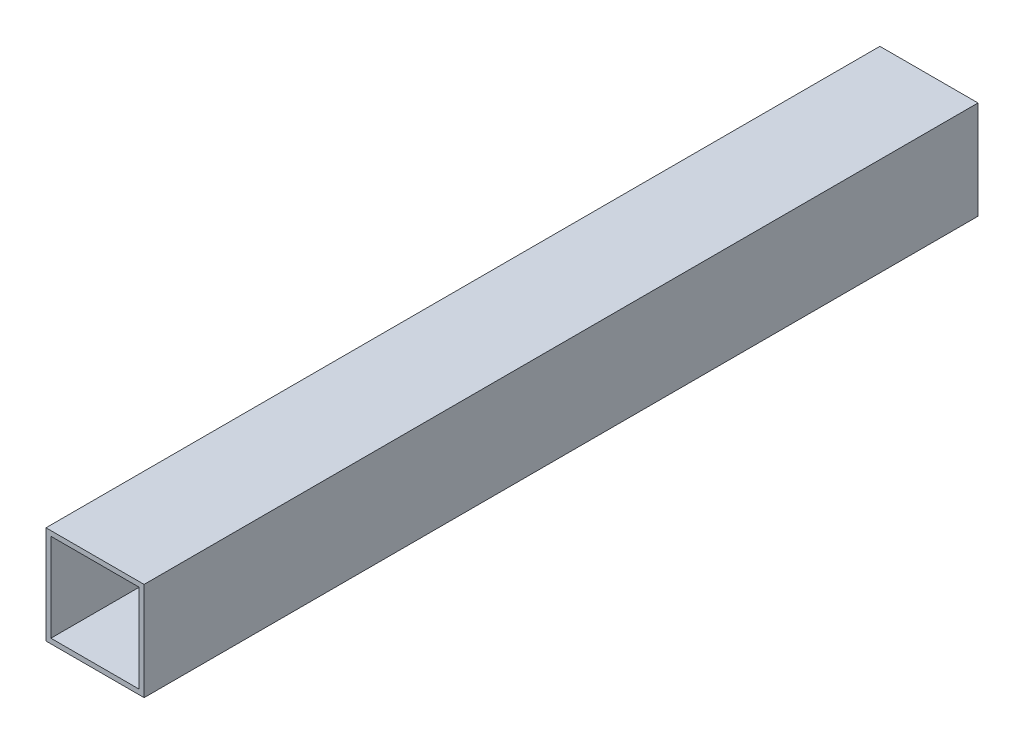
SolidWorks part; units mm, degrees
ref_plane "Alzado" through (0, 0, 0) normal (0, 0, 1) x (1, 0, 0)
ref_plane "Planta" through (0, 0, 0) normal (0, 1, 0) x (1, 0, 0)
ref_plane "Vista lateral" through (0, 0, 0) normal (1, 0, 0) x (0, 0, -1)
sketch "Croquis1" plane through (0, 0, 0) normal (0, 0, 1) x (1, 0, 0)
  line L1 (20, -20) -> (-20, -20)
  line L2 (20, -20) -> (20, 20)
  line L3 (20, 20) -> (-20, 20)
  line L4 (-20, -20) -> (-20, 20)
  line L5 (20, -20) -> (-20, 20) construction
  line L6 (20, 20) -> (-20, -20) construction
  point P0 (0, 0)
  dimension "D1" = 40
  dimension "D2" = 40
extrude "Extruir-Lámina1" add sketch "Croquis1" along normal blind 340 thin
